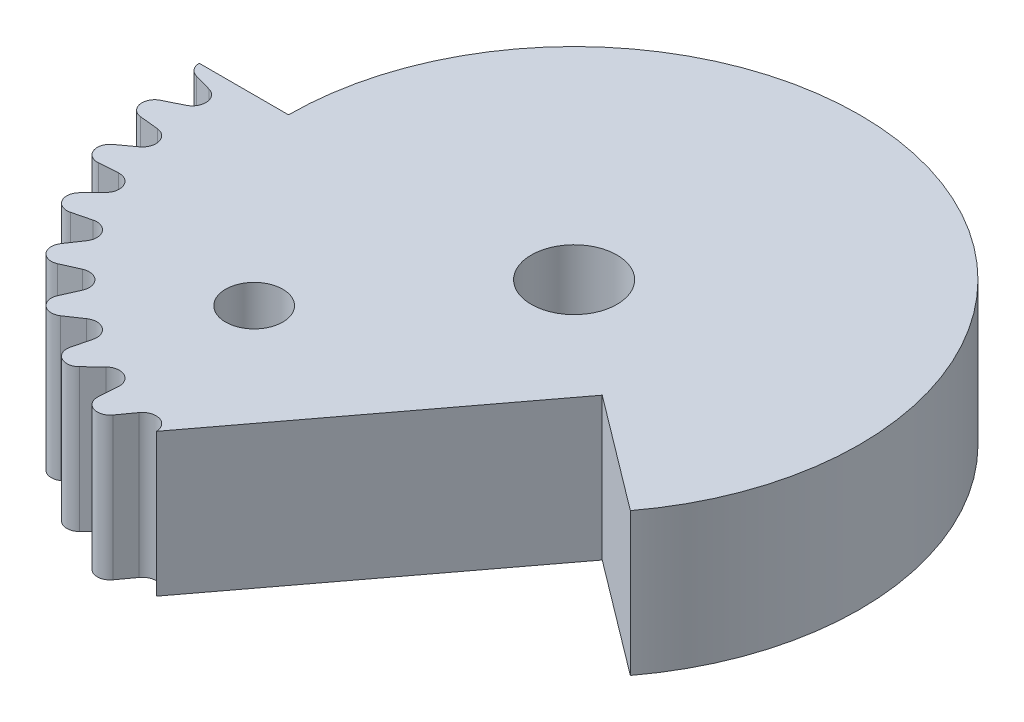
SolidWorks part; units mm, degrees
ref_plane "Plan de face" through (0, 0, 0) normal (0, 0, 1) x (1, 0, 0)
ref_plane "Plan de dessus" through (0, 0, 0) normal (0, 1, 0) x (1, 0, 0)
ref_plane "Plan de droite" through (0, 0, 0) normal (1, 0, 0) x (0, 0, -1)
sketch "Esquisse1" plane through (0, 0, 0) normal (0, 1, 0) x (1, 0, 0)
  line L0 (3.9932, -3.0091) -> (7.9864, -6.0182)
  line L1 (3.9932, -3.0091) -> (-2.7132, -11.9087)
  line L2 (0, 19.8747) -> (0, -20.8896) construction
  line L3 (39.5353, 0) -> (-39.5353, 0) construction
  line L4 (-10, 0) -> (-13.125, 0)
  line L5 (0, 0) -> (3.9932, -3.0091) construction
  line L6 (-2.7132, -11.9087) -> (-2.7166, -11.8761)
  line L7 (9.2936, 12.3331) -> (-17.3903, -23.0777) construction
  line L8 (-4.784, -11.8788) -> (-4.7376, -11.224)
  line L9 (-3.9708, -12.1748) -> (-3.5854, -11.6433)
  line L10 (-6.774, -10.8676) -> (-6.6146, -10.2308)
  line L11 (-6.0246, -11.3003) -> (-5.5528, -10.8438)
  line L12 (-8.5583, -9.5262) -> (-8.2907, -8.9267)
  line L13 (-7.8953, -10.0824) -> (-7.3515, -9.7148)
  line L14 (-10.0824, -7.8953) -> (-9.7148, -7.3515)
  line L15 (-9.5262, -8.5583) -> (-8.9267, -8.2907)
  line L16 (-11.3003, -6.0246) -> (-10.8438, -5.5528)
  line L17 (-10.8676, -6.774) -> (-10.2308, -6.6146)
  line L18 (-12.1748, -3.9708) -> (-11.6433, -3.5854)
  line L19 (-11.8788, -4.784) -> (-11.224, -4.7376)
  line L20 (-12.6793, -1.7963) -> (-12.089, -1.5091)
  line L21 (-12.5291, -2.6486) -> (-11.8761, -2.7166)
  line L23 (-12.7986, -0.4327) -> (-12.1674, -0.613)
  line L34 (-2.1286, -24.3298) -> (0, 0) construction
  circle A0 centre (-4.8145, -6.3891) radius 1
  circle A1 centre (0, 0) radius 1.5
  circle A2 centre (0, 0) radius 13.125 construction
  arc A4 (-4.784, -11.8788) -> (-3.9708, -12.1748) centre (-4.3351, -11.9106) ccw
  arc A5 (-6.774, -10.8676) -> (-6.0246, -11.3003) centre (-6.3375, -10.9769) ccw
  arc A6 (-8.5583, -9.5262) -> (-7.8953, -10.0824) centre (-8.1473, -9.7096) ccw
  arc A7 (-10.0824, -7.8953) -> (-9.5262, -8.5583) centre (-9.7096, -8.1473) ccw
  arc A8 (-11.3003, -6.0246) -> (-10.8676, -6.774) centre (-10.9769, -6.3375) ccw
  arc A9 (-12.1748, -3.9708) -> (-11.8788, -4.784) centre (-11.9106, -4.3351) ccw
  arc A10 (-12.6793, -1.7963) -> (-12.5291, -2.6486) centre (-12.4824, -2.201) ccw
  arc A12 (-13.125, 0) -> (-12.7986, -0.4327) centre (-12.675, 0) ccw
  arc A13 (7.9864, -6.0182) -> (-10, 0) centre (0, 0) ccw
  arc A14 (-2.7166, -11.8761) -> (-3.5854, -11.6433) centre (-3.1956, -11.926) ccw
  arc A15 (-4.7376, -11.224) -> (-5.5528, -10.8438) centre (-5.2179, -11.1899) ccw
  arc A16 (-6.6146, -10.2308) -> (-7.3515, -9.7148) centre (-7.0818, -10.1138) ccw
  arc A17 (-8.2907, -8.9267) -> (-8.9267, -8.2907) centre (-8.7304, -8.7304) ccw
  arc A18 (-9.7148, -7.3515) -> (-10.2308, -6.6146) centre (-10.1138, -7.0818) ccw
  arc A20 (-10.8438, -5.5528) -> (-11.224, -4.7376) centre (-11.1899, -5.2179) ccw
  arc A21 (-11.6433, -3.5854) -> (-11.8761, -2.7166) centre (-11.926, -3.1956) ccw
  arc A22 (-12.089, -1.5091) -> (-12.1674, -0.613) centre (-12.2997, -1.0761) ccw
  point P62 (0, 0)
  point P66 (0, 0)
  point P69 (0, 0)
  point P88 (0, 0)
  point P92 (0, 0)
  point P143 (0, 0)
  dimension "D1" = 3
  dimension "D2" = 5
  dimension "D6" = 5
  dimension "D7" = 26.25
  dimension "D4" = 8
  dimension "D5" = 37
  dimension "D3" = 2
extrude "Boss.-Extru.1" add sketch "Esquisse1" along normal blind 5
